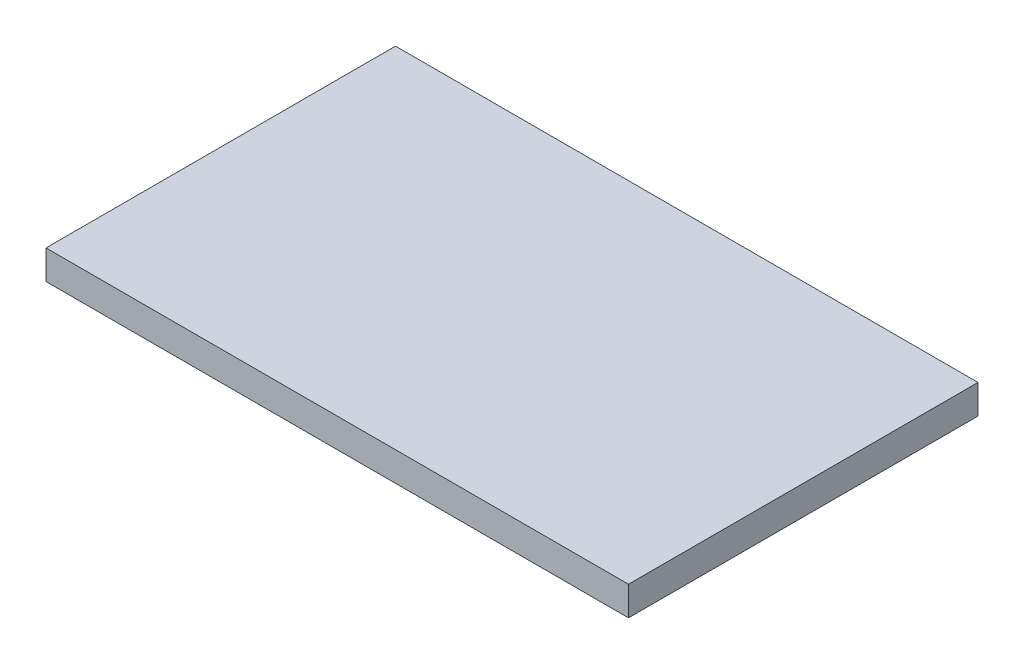
SolidWorks part; units mm, degrees
ref_plane "Front Plane" through (0, 0, 0) normal (0, 0, 1) x (1, 0, 0)
ref_plane "Top Plane" through (0, 0, 0) normal (0, 1, 0) x (1, 0, 0)
ref_plane "Right Plane" through (0, 0, 0) normal (1, 0, 0) x (0, 0, -1)
sketch "Sketch1" plane through (0, 0, 0) normal (0, 1, 0) x (1, 0, 0)
  line L1 (-31.75, -19.05) -> (31.75, -19.05)
  line L2 (-31.75, -19.05) -> (-31.75, 19.05)
  line L3 (-31.75, 19.05) -> (31.75, 19.05)
  line L4 (31.75, -19.05) -> (31.75, 19.05)
  line L5 (-31.75, -19.05) -> (31.75, 19.05) construction
  line L6 (-31.75, 19.05) -> (31.75, -19.05) construction
  point P1 (0, 0)
  dimension "D1" = 63.5
  dimension "D2" = 38.1
extrude "Boss-Extrude1" add sketch "Sketch1" along normal blind 3.175
